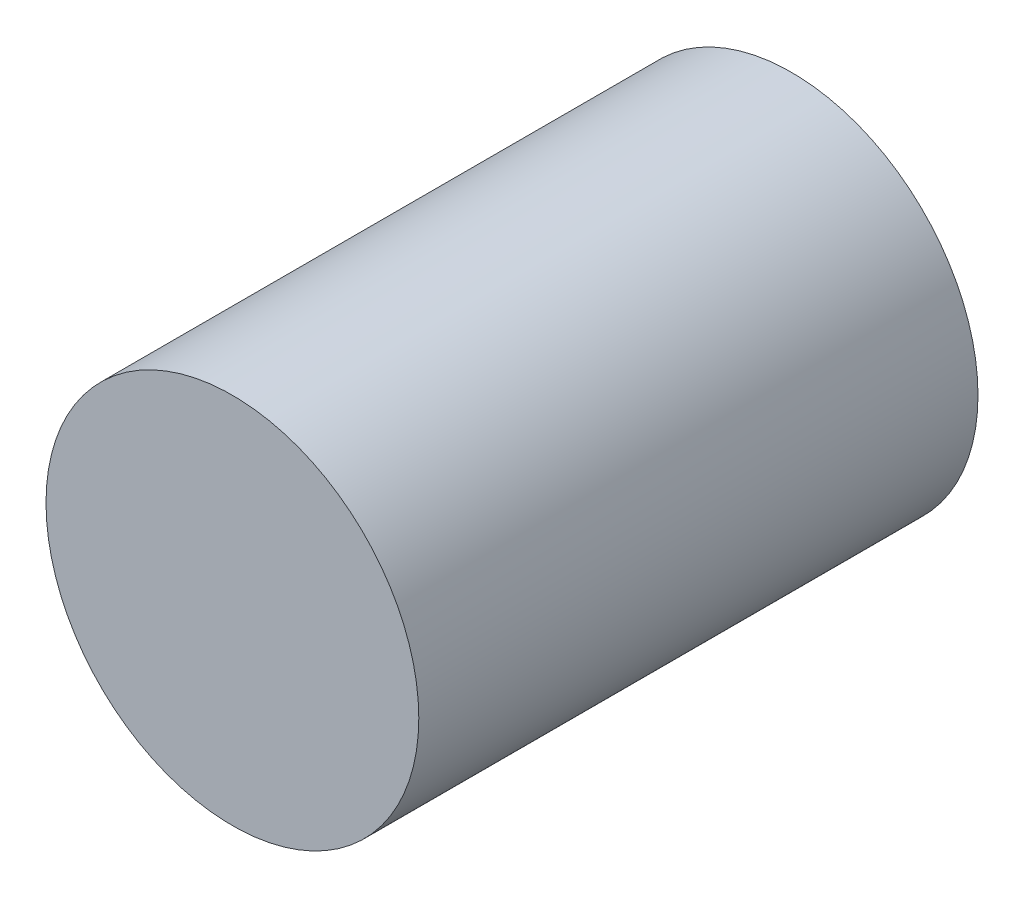
SolidWorks part; units mm, degrees
material "AISI 304"
ref_plane "Front Plane" through (0, 0, 0) normal (0, 0, 1) x (1, 0, 0)
ref_plane "Top Plane" through (0, 0, 0) normal (0, 1, 0) x (1, 0, 0)
ref_plane "Right Plane" through (0, 0, 0) normal (1, 0, 0) x (0, 0, -1)
sketch "Croquis1" plane through (0, 0, 0) normal (0, 0, 1) x (1, 0, 0)
  circle A0 centre (0, 0) radius 10
  dimension "D1" = 20
extrude "Saliente-Extruir1" add sketch "Croquis1" along normal blind 30
